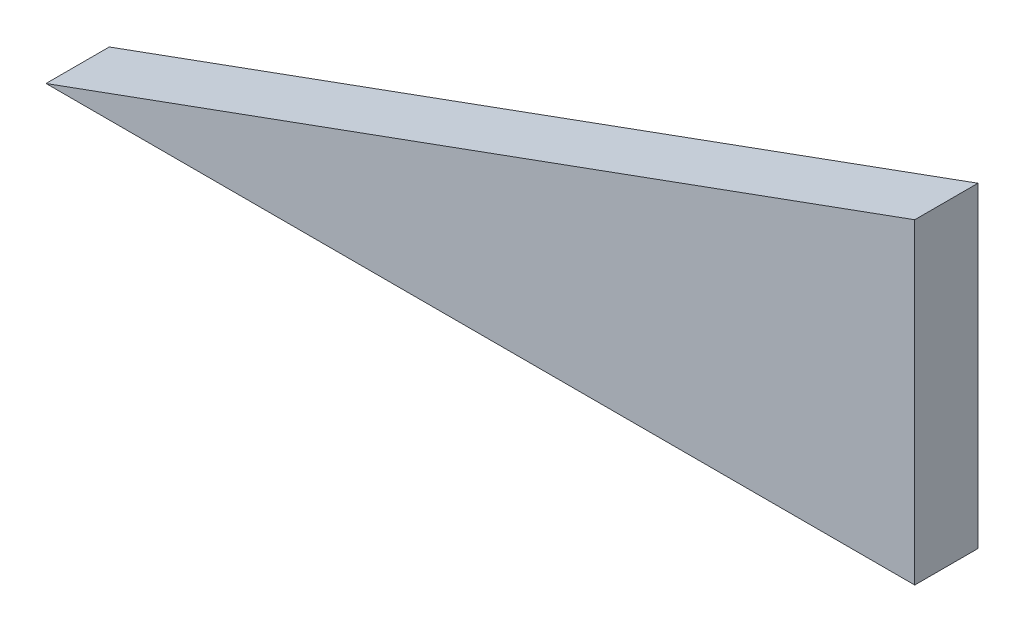
SolidWorks part; units mm, degrees
ref_plane "Front Plane" through (0, 0, 0) normal (0, 0, 1) x (1, 0, 0)
ref_plane "Top Plane" through (0, 0, 0) normal (0, 1, 0) x (1, 0, 0)
ref_plane "Right Plane" through (0, 0, 0) normal (1, 0, 0) x (0, 0, -1)
sketch "Sketch1" plane through (0, 0, 0) normal (0, 0, 1) x (1, 0, 0)
  line L0 (0, 0) -> (-412, 0)
  line L1 (0, 0) -> (0, 150.0372)
  line L2 (0, 150.0372) -> (-412, 0)
  dimension "D1" = 20.01
  dimension "D2" = 412
extrude "Boss-Extrude1" add sketch "Sketch1" along normal blind 30
